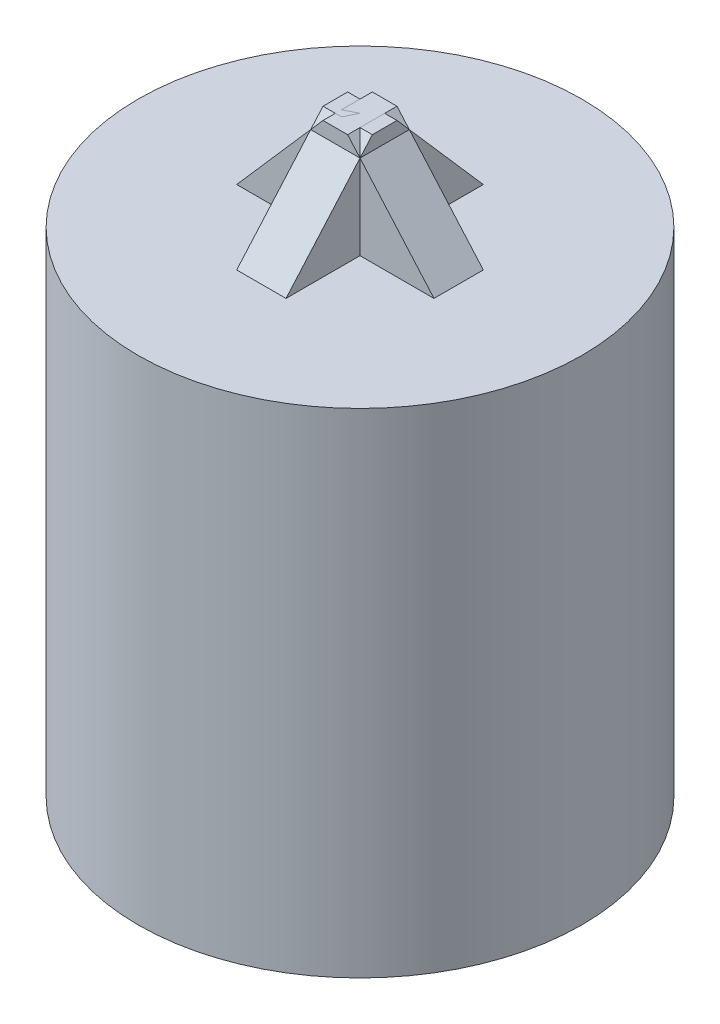
SolidWorks part; units mm, degrees
ref_plane "Front" through (0, 0, 0) normal (0, 0, 1) x (1, 0, 0)
ref_plane "Top" through (0, 0, 0) normal (0, 1, 0) x (1, 0, 0)
ref_plane "Right" through (0, 0, 0) normal (1, 0, 0) x (0, 0, -1)
sketch "Эскиз1" plane through (0, 0, 0) normal (0, 1, 0) x (1, 0, 0)
  line L0 (0, -4.5) -> (0, 4.5) construction
  line L1 (1, 1.5) -> (-1.5, 1.5)
  line L2 (1, 1.5) -> (1, -1.5)
  line L3 (1, -1.5) -> (-1.5, -1.5)
  line L4 (-1.5, 1.5) -> (-1.5, -1.5)
  line L5 (-4.5, 0) -> (4.5, 0) construction
  circle A0 centre (0, 0) radius 4.5
  dimension "D1" = 9
  dimension "D2" = 1.5
  dimension "D3" = 3
  dimension "D4" = 1
extrude "Бобышка-Вытянуть1" add sketch "Эскиз1" along normal blind 10 contours L1 L4 L3 L2 | A0 L4 L1 L2 L3
sketch "Эскиз2" plane through (0, 0, 0) normal (0, 1, 0) x (1, 0, 0)
  line L0 (0, -4.5) -> (0, 4.5) construction
  line L1 (1, 1.5) -> (-1.5, 1.5)
  line L2 (1, 1.5) -> (1, -1.5)
  line L3 (1, -1.5) -> (-1.5, -1.5)
  line L4 (-1.5, 1.5) -> (-1.5, -1.5)
  line L5 (-4.5, 0) -> (4.5, 0) construction
  circle A0 centre (0, 0) radius 4.5
  circle A1 centre (0, 0) radius 4.5 construction
extrude "Вырез-Вытянуть1" cut sketch "Эскиз2" along normal blind 9 contours L4 L1 L2 L3
sketch "Эскиз3" plane through (0, 0, 0) normal (0, 0, 1) x (1, 0, 0)
  line L0 (0, 10) -> (0, 12.3778) construction
  line L1 (4.5, 10) -> (-4.5, 10) construction
  line L2 (2, 10) -> (-2, 10)
  line L3 (-2, 10) -> (-0.25, 12)
  line L4 (-0.25, 12) -> (0.25, 12)
  line L5 (0.25, 12) -> (2, 10)
  dimension "D1" = 2
  dimension "D2" = 4
  dimension "D3" = 0.5
extrude "Бобышка-Вытянуть2" add sketch "Эскиз3" along normal mid plane 1
sketch "Эскиз4" plane through (0, 0, 0) normal (1, 0, 0) x (0, 0, -1)
  line L0 (0, 10) -> (0, 12.3778) construction
  line L1 (-0.5, 12) -> (0.5, 12) construction
  line L2 (2, 10) -> (-2, 10)
  line L3 (-2, 10) -> (-0.25, 12)
  line L4 (-0.25, 12) -> (0.25, 12)
  line L5 (0.25, 12) -> (2, 10)
extrude "Бобышка-Вытянуть3" add sketch "Эскиз4" along normal mid plane 1 separate body
